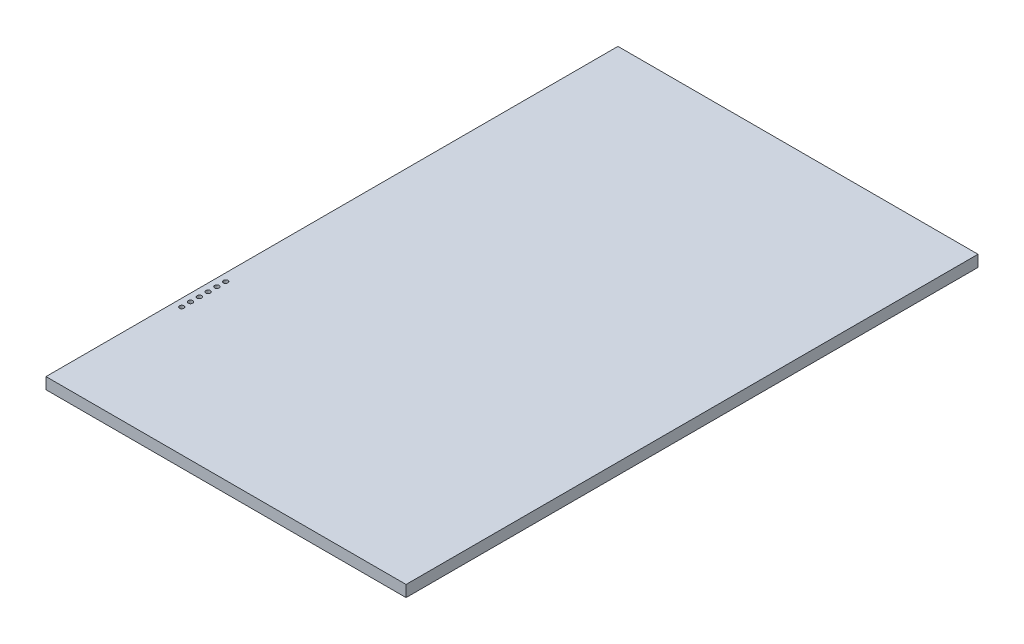
SolidWorks part; units mm, degrees
ref_plane "Front Plane" through (0, 0, 0) normal (0, 0, 1) x (1, 0, 0)
ref_plane "Top Plane" through (0, 0, 0) normal (0, 1, 0) x (1, 0, 0)
ref_plane "Right Plane" through (0, 0, 0) normal (1, 0, 0) x (0, 0, -1)
sketch "Sketch1" plane through (0, 0, 0) normal (0, 1, 0) x (1, 0, 0)
  line L1 (0, 0) -> (52, 0)
  line L2 (0, 0) -> (0, 82.6)
  line L3 (0, 82.6) -> (52, 82.6)
  line L4 (52, 0) -> (52, 82.6)
  dimension "D1" = 52
  dimension "D2" = 82.6
extrude "Boss-Extrude1" add sketch "Sketch1" along normal blind 1.65
sketch "Sketch2" plane through (0, 0, 0) normal (0, 1, 0) x (1, 0, 0)
  circle A0 centre (1.1, 18.5) radius 0.325
  point P2 (17.174, 11.7093)
  dimension "D1" = 0.65
  dimension "D2" = 1.1
  dimension "D3" = 18.5
extrude "Cut-Extrude4" cut sketch "Sketch2" along normal through all contours A0
pattern_linear "LPattern1" count 6 spacing 1.27 along (0, 0, -1) of "Cut-Extrude4"
